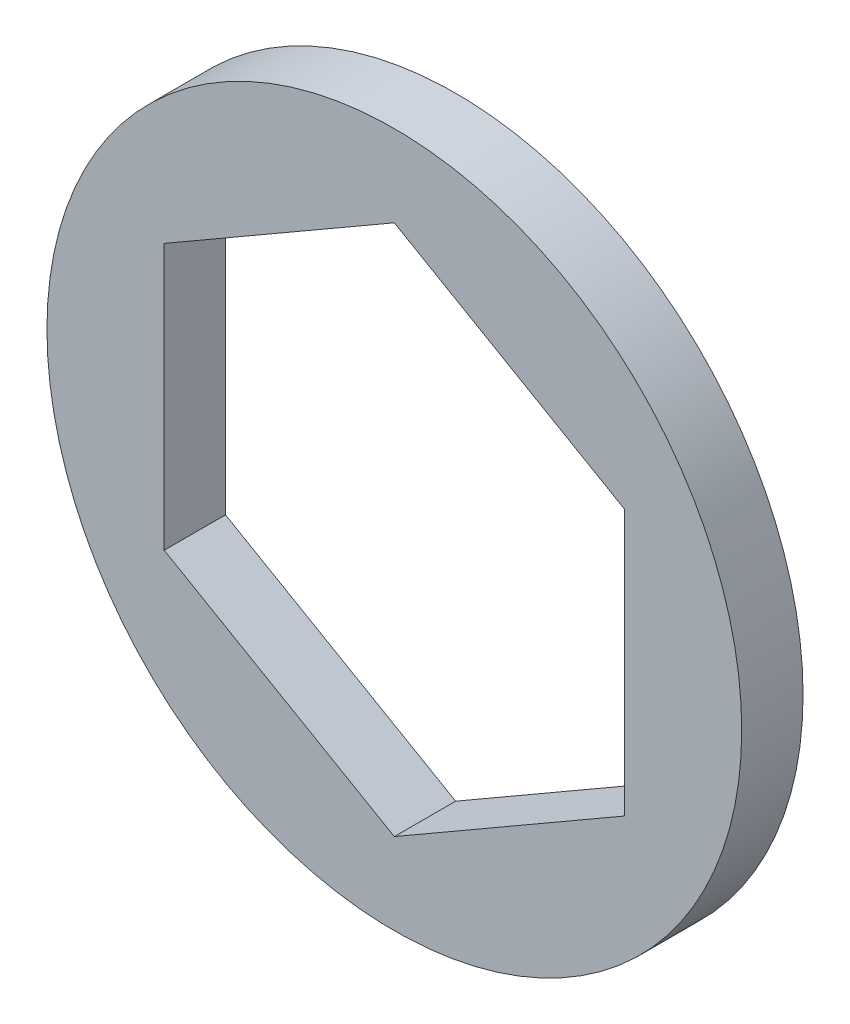
SolidWorks part; units mm, degrees
material "Nylon 101"
ref_plane "Front Plane" through (0, 0, 0) normal (0, 0, 1) x (1, 0, 0)
ref_plane "Top Plane" through (0, 0, 0) normal (0, 1, 0) x (1, 0, 0)
ref_plane "Right Plane" through (0, 0, 0) normal (1, 0, 0) x (0, 0, -1)
sketch "Sketch1" plane through (0, 0, 0) normal (0, 0, 1) x (1, 0, 0)
  line L1 (6.731, 3.8861) -> (0, 7.7723)
  line L2 (0, 7.7723) -> (-6.731, 3.8861)
  line L3 (-6.731, 3.8861) -> (-6.731, -3.8861)
  line L4 (-6.731, -3.8861) -> (0, -7.7723)
  line L5 (0, -7.7723) -> (6.731, -3.8861)
  line L6 (6.731, -3.8861) -> (6.731, 3.8861)
  circle A0 centre (0, 0) radius 6.731 construction
  circle A1 centre (0, 0) radius 10.16
  dimension "D1" = 13.462
  dimension "D2" = 20.32
extrude "Boss-Extrude1" add sketch "Sketch1" along normal blind 1.7935
